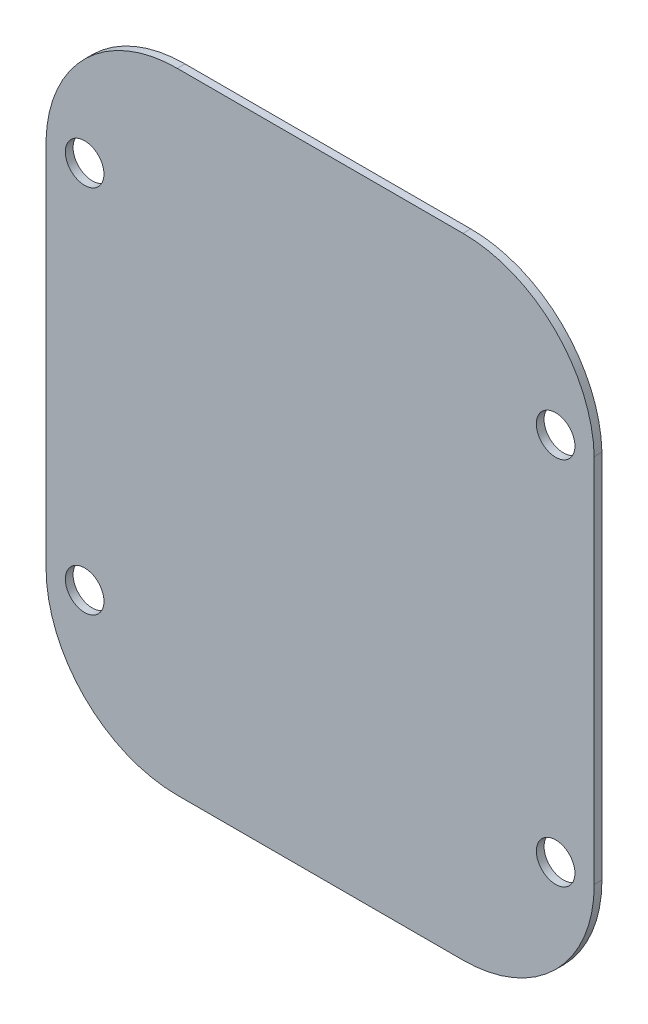
SolidWorks part; units mm, degrees
material "AISI 304"
ref_plane "Front Plane" through (0, 0, 0) normal (0, 0, 1) x (1, 0, 0)
ref_plane "Top Plane" through (0, 0, 0) normal (0, 1, 0) x (1, 0, 0)
ref_plane "Right Plane" through (0, 0, 0) normal (1, 0, 0) x (0, 0, -1)
sketch "Sketch1" plane through (0, 0, 0) normal (0, 0, 1) x (1, 0, 0)
  line L0 (92.5614, 203.8985) -> (-92.5614, 203.8985)
  line L1 (-177.5614, 121.1015) -> (-177.5614, -118.8985)
  line L2 (-92.5614, -203.8985) -> (92.5614, -203.8985)
  line L3 (177.5614, -118.8985) -> (177.5614, 121.1015)
  line L4 (0, 203.8985) -> (0, -203.8985) construction
  arc A0 (177.5614, 121.1015) -> (92.5614, 203.8985) centre (92.59, 118.8985) ccw
  arc A1 (-92.5614, 203.8985) -> (-177.5614, 121.1015) centre (-92.59, 118.8985) ccw
  arc A2 (-177.5614, -118.8985) -> (-92.5614, -203.8985) centre (-92.5614, -118.8985) ccw
  arc A3 (92.5614, -203.8985) -> (177.5614, -118.8985) centre (92.5614, -118.8985) ccw
  dimension "D3" = 85
  dimension "D1" = 355.1228
  dimension "D2" = 407.7969
extrude "Boss-Extrude1" add sketch "Sketch1" along normal blind 5
sketch "Sketch2" plane through (0, 0, 5) normal (0, 0, 1) x (1, 0, 0)
  line L0 (92.5656, 178.8985) -> (-92.5656, 178.8985) construction
  line L1 (-152.5614, 120.7493) -> (-152.5614, -118.8985) construction
  line L2 (-92.5614, -178.8985) -> (92.5614, -178.8985) construction
  line L3 (152.5614, -118.8985) -> (152.5614, 120.7493) construction
  line L4 (92.5614, 203.8985) -> (-92.5614, 203.8985)
  line L5 (-177.5614, 121.1015) -> (-177.5614, -118.8985)
  line L6 (-92.5614, -203.8985) -> (92.5614, -203.8985)
  line L7 (177.5614, -118.8985) -> (177.5614, 121.1015)
  line L8 (92.5614, 203.8985) -> (-92.5614, 203.8985)
  line L9 (-177.5614, 121.1015) -> (-177.5614, -118.8985)
  line L10 (-92.5614, -203.8985) -> (92.5614, -203.8985)
  line L11 (177.5614, -118.8985) -> (177.5614, 121.1015)
  arc A0 (-92.5656, 178.8985) -> (-152.5614, 120.7493) centre (-92.59, 118.8985) ccw construction
  arc A1 (-152.5614, -118.8985) -> (-92.5614, -178.8985) centre (-92.5614, -118.8985) ccw construction
  arc A2 (92.5614, -178.8985) -> (152.5614, -118.8985) centre (92.5614, -118.8985) ccw construction
  arc A3 (152.5614, 120.7493) -> (92.5656, 178.8985) centre (92.59, 118.8985) ccw construction
  arc A4 (177.5614, 121.1015) -> (92.5614, 203.8985) centre (92.59, 118.8985) ccw
  arc A5 (-92.5614, 203.8985) -> (-177.5614, 121.1015) centre (-92.59, 118.8985) ccw
  arc A6 (-177.5614, -118.8985) -> (-92.5614, -203.8985) centre (-92.5614, -118.8985) ccw
  arc A7 (92.5614, -203.8985) -> (177.5614, -118.8985) centre (92.5614, -118.8985) ccw
  arc A8 (177.5614, 121.1015) -> (92.5614, 203.8985) centre (92.59, 118.8985) ccw
  arc A9 (-92.5614, 203.8985) -> (-177.5614, 121.1015) centre (-92.59, 118.8985) ccw
  arc A10 (-177.5614, -118.8985) -> (-92.5614, -203.8985) centre (-92.5614, -118.8985) ccw
  arc A11 (92.5614, -203.8985) -> (177.5614, -118.8985) centre (92.5614, -118.8985) ccw
  circle A12 centre (-152.5614, 120.7493) radius 12.5
  circle A13 centre (-152.5614, -118.8985) radius 12.5
  circle A14 centre (152.5614, -118.8985) radius 12.5
  circle A15 centre (152.5614, 120.7493) radius 12.5
  dimension "D3" = 25
  dimension "D1" = 0
  dimension "D2" = 25
extrude "Cut-Extrude1" cut sketch "Sketch2" against normal blind 5 contours A12 | A15 | A13 | A14
